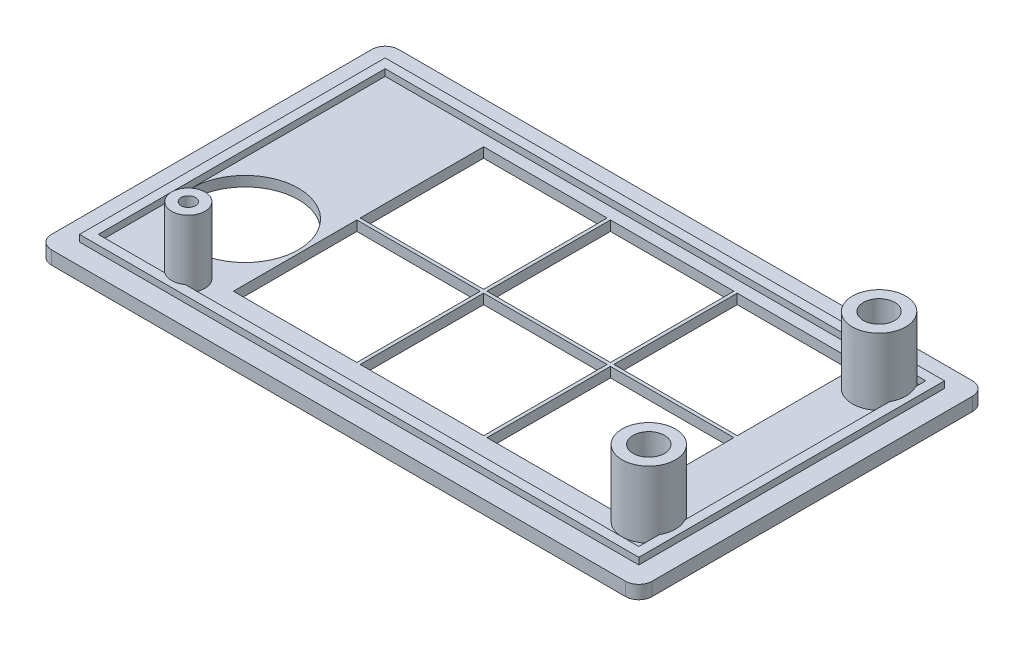
SolidWorks part; units mm, degrees
ref_plane "Front Plane" through (0, 0, 0) normal (0, 0, 1) x (1, 0, 0)
ref_plane "Top Plane" through (0, 0, 0) normal (0, 1, 0) x (1, 0, 0)
ref_plane "Right Plane" through (0, 0, 0) normal (1, 0, 0) x (0, 0, -1)
sketch "Sketch3" plane through (0, 0, 0) normal (0, 1, 0) x (1, 0, 0)
  line L0 (-45, 26) -> (45, 26)
  line L1 (-45, 26) -> (-45, -26)
  line L2 (-45, -26) -> (45, -26)
  line L3 (45, 26) -> (45, -26)
  dimension "D1" = 90
  dimension "D2" = 52
  dimension "D3" = 45
  dimension "D4" = 26
extrude "Boss-Extrude2" add sketch "Sketch3" along normal blind 2
fillet "Fillet2" radius 2 4 edges at (-45, 1, 26) (45, 1, 26) (45, 1, -26) (-45, 1, -26)
sketch "Sketch4" plane through (0, 0, 0) normal (0, 1, 0) x (1, 0, 0)
  line L1 (-41.5, 22.5) -> (41.5, 22.5)
  line L2 (-41.5, 22.5) -> (-41.5, -22.5)
  line L3 (-41.5, -22.5) -> (41.5, -22.5)
  line L4 (41.5, 22.5) -> (41.5, -22.5)
  dimension "D1" = 83
  dimension "D2" = 45
  dimension "D3" = 41.5
  dimension "D4" = 22.5
sketch "Sketch5" plane through (0, 0, 0) normal (0, 1, 0) x (1, 0, 0)
  line L46 (-41.5, 22.5) -> (-41.5, -22.5) construction
  line L47 (-41.5, -22.5) -> (41.5, -22.5) construction
  line L102 (-24, 19.75) -> (-5.5, 19.75)
  line L103 (32.5, 19.75) -> (32.5, 1.25)
  line L104 (-24, -17.75) -> (-5.5, -17.75)
  line L105 (-24, 19.75) -> (-24, 1.25)
  line L106 (-24, 0.75) -> (-24, -17.75)
  line L107 (-24, 1.25) -> (-5.5, 1.25)
  line L109 (-24, 0.75) -> (-5.5, 0.75)
  line L111 (32.5, 0.75) -> (32.5, -17.75)
  line L112 (-5, 19.75) -> (13.5, 19.75)
  line L114 (-5.5, 19.75) -> (-5.5, 1.25)
  line L116 (-5, 19.75) -> (-5, 1.25)
  line L118 (13.5, 19.75) -> (13.5, 1.25)
  line L120 (14, 19.75) -> (14, 1.25)
  line L121 (14, 19.75) -> (32.5, 19.75)
  line L122 (14, 1.25) -> (32.5, 1.25)
  line L123 (14, 0.75) -> (32.5, 0.75)
  line L124 (-5, 1.25) -> (13.5, 1.25)
  line L125 (-5, 0.75) -> (13.5, 0.75)
  line L126 (-5, 0.75) -> (-5, -17.75)
  line L127 (-5.5, 0.75) -> (-5.5, -17.75)
  line L128 (13.5, 0.75) -> (13.5, -17.75)
  line L129 (14, 0.75) -> (14, -17.75)
  line L130 (-5, -17.75) -> (13.5, -17.75)
  line L131 (14, -17.75) -> (32.5, -17.75)
  circle A32 centre (-32.5, -7.5) radius 8
  point P26 (0, 0)
  point P27 (0, 0)
  point P28 (0, 0)
  point P29 (0, 0)
  dimension "D3" = 56.5
  dimension "D11" = 0.5
  dimension "D16" = 9
  dimension "D14" = 16
  dimension "D2" = 24
  dimension "D4" = 37.5
  dimension "D5" = 19.75
  dimension "D6" = 0.5
  dimension "D7" = 18.5
  dimension "D8" = 18.5
  dimension "D9" = 18.5
  dimension "D10" = 18.5
  dimension "D15" = 15
sketch "Sketch7" plane through (0, 0, 0) normal (0, 1, 0) x (1, 0, 0)
  line L2 (41.5, 22.5) -> (41.5, -22.5) construction
  line L3 (-41.5, -22.5) -> (41.5, -22.5) construction
  circle A0 centre (37, 18) radius 4
  circle A3 centre (37, -16.5) radius 4
  dimension "D4" = 4.5
  dimension "D5" = 6
extrude "Boss-Extrude3" add sketch "Sketch7" along normal blind 10 from surface at 2 starting at face at (0, 2, 0)
sketch "Sketch8" plane through (0, 0, 0) normal (0, 1, 0) x (1, 0, 0)
  circle A1 centre (37, 18) radius 2.35
  circle A2 centre (37, -16.5) radius 2.35
  dimension "D1" = 4.7
extrude "Cut-Extrude2" cut sketch "Sketch8" against normal blind 4 and the other way through all from surface at 2 starting at face at (37, 2, -14)
sketch "Sketch10" plane through (0, 0, 0) normal (0, 1, 0) x (1, 0, 0)
  line L4 (40.5, 21.5) -> (-40.5, 21.5)
  line L5 (-40.5, 21.5) -> (-40.5, -21.5)
  line L6 (-40.5, -21.5) -> (40.5, -21.5)
  line L7 (40.5, -21.5) -> (40.5, 21.5)
  line L8 (41.9, 22.9) -> (-41.9, 22.9)
  line L9 (41.9, -22.9) -> (41.9, 22.9)
  line L10 (-41.9, -22.9) -> (41.9, -22.9)
  line L11 (-41.9, 22.9) -> (-41.9, -22.9)
  line L12 (41.9, 22.9) -> (-41.9, 22.9)
  line L13 (41.9, -22.9) -> (41.9, 22.9)
  line L14 (-41.9, -22.9) -> (41.9, -22.9)
  line L15 (-41.9, 22.9) -> (-41.9, -22.9)
  dimension "D1" = 0.4
  dimension "D2" = 1.4
extrude "Boss-Extrude4" add sketch "Sketch10" along normal blind 1 from surface at 2 starting at face at (37, 2, -14)
sketch "Sketch11" plane through (0, 0, 0) normal (0, 1, 0) x (1, 0, 0)
  line L0 (-41.5, -22.5) -> (41.5, -22.5) construction
  circle A0 centre (-29, -19.5) radius 2.5
  dimension "D2" = 5
  dimension "D1" = 3
  dimension "D3" = 11.5
extrude "Boss-Extrude5" add sketch "Sketch11" along normal blind 10 from surface at 2 starting at face at (14.9933, 2, 2.9352)
sketch "Sketch12" plane through (0, 0, 0) normal (0, 1, 0) x (1, 0, 0)
  circle A0 centre (-29, -19.5) radius 1.075
  dimension "D1" = 2.15
extrude "Cut-Extrude3" cut sketch "Sketch12" against normal blind 10 from surface at 12 starting at face at (-29, 12, 22)
extrude "Cut-Extrude4" cut sketch "Sketch4" along normal blind 0.5
extrude "Cut-Extrude5" cut sketch "Sketch5" along normal through all both and the other way through all
